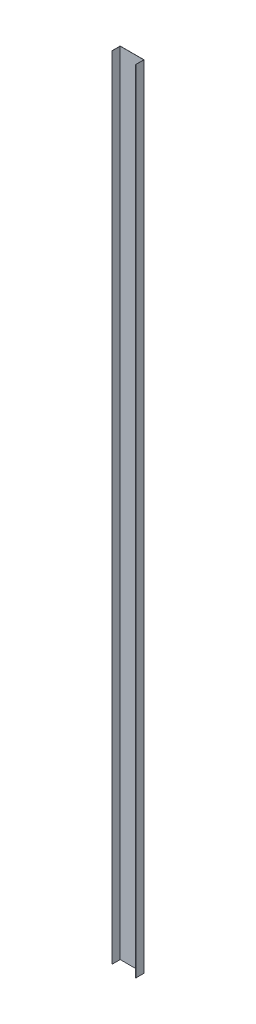
SolidWorks part; units mm, degrees
ref_plane "Front Plane" through (0, 0, 0) normal (0, 0, 1) x (1, 0, 0)
ref_plane "Top Plane" through (0, 0, 0) normal (0, 1, 0) x (1, 0, 0)
ref_plane "Right Plane" through (0, 0, 0) normal (1, 0, 0) x (0, 0, -1)
sketch "Sketch1" plane through (0, 0, 0) normal (0, 1, 0) x (1, 0, 0)
  line L0 (0, 0) -> (0, 31.219)
  line L1 (0, 31.219) -> (91.013, 31.219)
  line L2 (91.013, 31.219) -> (91.013, 0)
  line L3 (91.013, 0) -> (91.544, 0)
  line L4 (91.544, 0) -> (91.544, 31.75)
  line L5 (91.544, 31.75) -> (-0.531, 31.75)
  line L6 (-0.531, 31.75) -> (-0.531, 0)
  line L7 (-0.531, 0) -> (0, 0)
  line L8 (45.5065, 31.75) -> (45.5065, 31.219) construction
  dimension "D1" = 0.531
  dimension "D2" = 92.075
  dimension "D3" = 31.75
extrude "Boss-Extrude1" add sketch "Sketch1" along normal blind 3048
